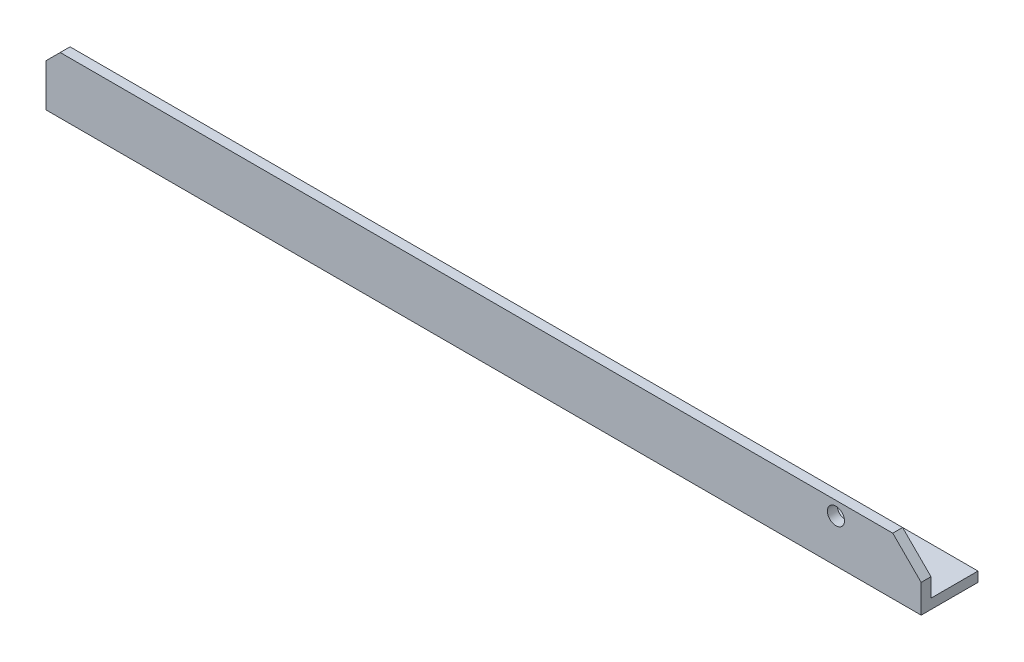
SolidWorks part; units mm, degrees
ref_plane "Front Plane" through (0, 0, 0) normal (0, 0, 1) x (1, 0, 0)
ref_plane "Top Plane" through (0, 0, 0) normal (0, 1, 0) x (1, 0, 0)
ref_plane "Right Plane" through (0, 0, 0) normal (1, 0, 0) x (0, 0, -1)
sketch "Sketch1" plane through (0, 0, 0) normal (1, 0, 0) x (0, 0, -1)
  line L0 (0, 0) -> (20, 0)
  line L1 (20, 0) -> (20, 3.4612)
  line L2 (20, 3.4612) -> (3.4612, 3.4612)
  line L3 (3.4612, 3.4612) -> (3.4612, 20)
  line L4 (3.4612, 20) -> (0, 20)
  line L5 (0, 20) -> (0, 0)
  dimension "D1" = 3.4612
  dimension "D2" = 20
extrude "Boss-Extrude1" add sketch "Sketch1" along normal blind 308
sketch "Sketch2" plane through (0, 0, 0) normal (0, 0, 1) x (1, 0, 0)
  line L0 (308, 20) -> (308, 0) construction
  line L1 (308, 0) -> (0, 0) construction
  line L2 (308, 10) -> (298, 20)
  line L3 (308, 20) -> (0, 20) construction
  line L4 (298, 20) -> (308, 20)
  line L5 (308, 20) -> (308, 10)
  line L6 (5, 20) -> (0, 20)
  line L7 (0, 20) -> (0, 15)
  line L8 (0, 20) -> (0, 0) construction
  line L9 (0, 15) -> (5, 20)
  circle A0 centre (278, 15.25) radius 3
  dimension "D1" = 6
  dimension "D2" = 30
  dimension "D3" = 15.25
  dimension "D4" = 10
  dimension "D5" = 5
extrude "Cut-Extrude1" cut sketch "Sketch2" against normal through all
